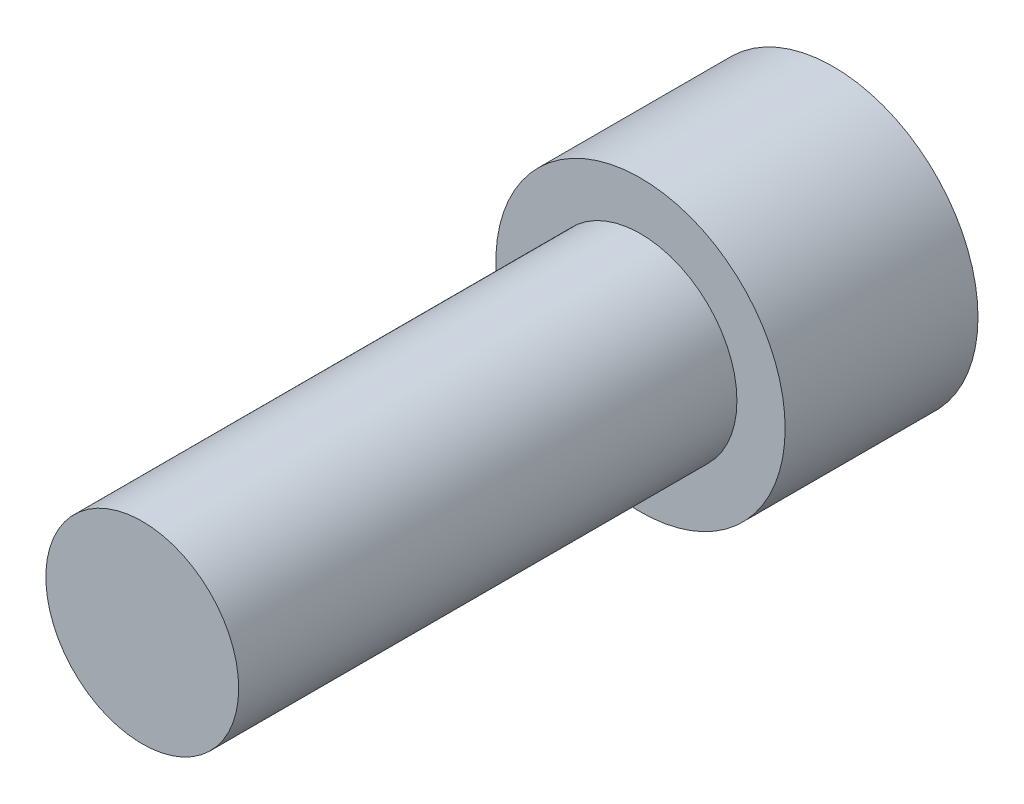
SolidWorks part; units mm, degrees
ref_plane "正面" through (0, 0, 0) normal (0, 0, 1) x (1, 0, 0)
ref_plane "平面" through (0, 0, 0) normal (0, 1, 0) x (1, 0, 0)
ref_plane "右側面" through (0, 0, 0) normal (1, 0, 0) x (0, 0, -1)
sketch "ｽｹｯﾁ1" plane through (0, 0, 0) normal (0, 0, 1) x (1, 0, 0)
  circle A0 centre (0, 0) radius 9
  dimension "D1" = 18
extrude "ﾎﾞｽ - 押し出し1" add sketch "ｽｹｯﾁ1" along normal blind 12 contours A0
sketch "ｽｹｯﾁ2" plane through (0, 0, 12) normal (0, 0, 1) x (1, 0, 0)
  circle A0 centre (0, 0) radius 6
  dimension "D1" = 12
extrude "ﾎﾞｽ - 押し出し2" add sketch "ｽｹｯﾁ2" along normal blind 31
cosmetic thread "ねじ山1" parameters "D2"=11
sketch "ｽｹｯﾁ3" plane through (0, 0, 0) normal (0, 0, -1) x (-1, 0, 0)
  line L1 (5.2109, 4.3676) -> (-1.177, 6.6966)
  line L2 (-1.177, 6.6966) -> (-6.3879, 2.3289)
  line L3 (-6.3879, 2.3289) -> (-5.2109, -4.3676)
  line L4 (-5.2109, -4.3676) -> (1.177, -6.6966)
  line L5 (1.177, -6.6966) -> (6.3879, -2.3289)
  line L6 (6.3879, -2.3289) -> (5.2109, 4.3676)
  circle A0 centre (0, 0) radius 5.8883 construction
extrude "ｶｯﾄ - 押し出し1" cut sketch "ｽｹｯﾁ3" against normal blind 3
